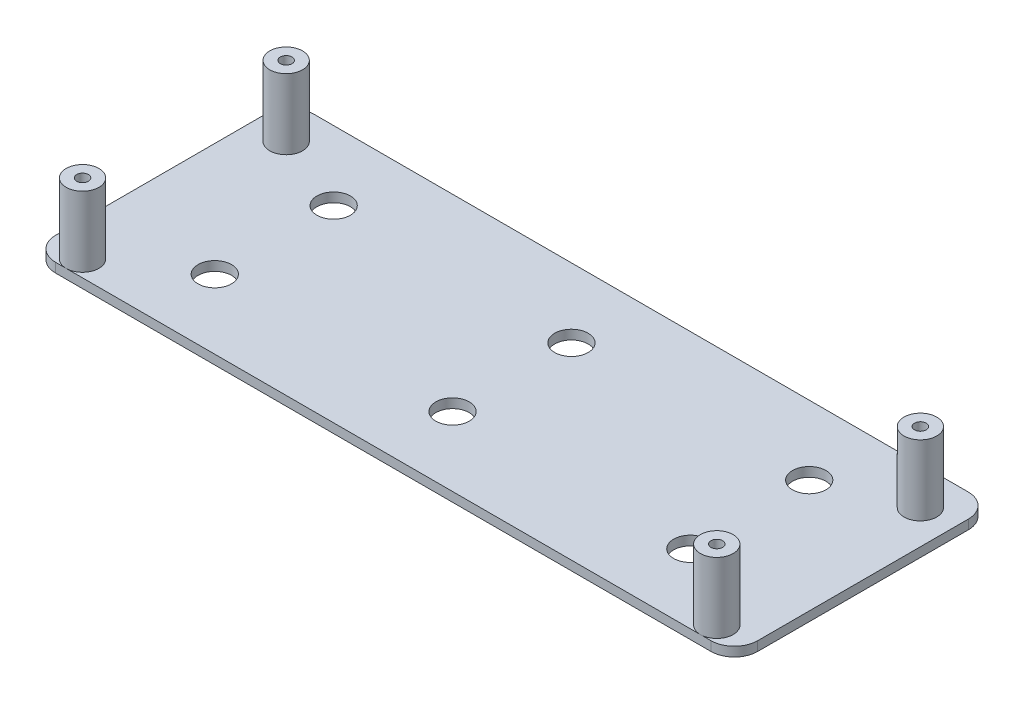
SolidWorks part; units mm, degrees
ref_plane "Front Plane" through (0, 0, 0) normal (0, 0, 1) x (1, 0, 0)
ref_plane "Top Plane" through (0, 0, 0) normal (0, 1, 0) x (1, 0, 0)
ref_plane "Right Plane" through (0, 0, 0) normal (1, 0, 0) x (0, 0, -1)
sketch "Sketch1" plane through (0, 0, 0) normal (0, 1, 0) x (1, 0, 0)
  line L1 (-75, -27.5) -> (75, -27.5)
  line L2 (-75, -27.5) -> (-75, 27.5)
  line L3 (-75, 27.5) -> (75, 27.5)
  line L4 (75, -27.5) -> (75, 27.5)
  line L5 (-75, -27.5) -> (75, 27.5) construction
  line L6 (-75, 27.5) -> (75, -27.5) construction
  line L7 (-67.75, -24) -> (67.75, -24) construction
  line L8 (-67.75, -24) -> (-67.75, 19.5) construction
  line L9 (-67.75, 19.5) -> (67.75, 19.5) construction
  line L10 (67.75, -24) -> (67.75, 19.5) construction
  point P0 (0, 0)
  point P10 (0, 19.5)
  dimension "D1" = 55
  dimension "D2" = 150
  dimension "D3" = 135.5
  dimension "D4" = 43.5
  dimension "D5" = 3.5
extrude "Boss-Extrude1" add sketch "Sketch1" along normal blind 2
sketch "Sketch2" plane through (0, 2, 0) normal (0, 1, 0) x (1, 0, 0)
  line L0 (-67.75, -24) -> (-67.75, 19.5) construction
  line L1 (-67.75, -24) -> (67.75, -24) construction
  line L2 (67.75, -24) -> (67.75, 19.5) construction
  line L3 (-67.75, 19.5) -> (67.75, 19.5) construction
  line L4 (-67.75, -24) -> (-67.75, 19.5) construction
  line L5 (-67.75, -24) -> (67.75, -24) construction
  line L6 (67.75, -24) -> (67.75, 19.5) construction
  line L7 (-67.75, 19.5) -> (67.75, 19.5) construction
  line L9 (-75, -27.5) -> (75, -27.5) construction
  circle A0 centre (-67.75, -24) radius 3.5
  circle A1 centre (-67.75, 19.5) radius 3.5
  circle A2 centre (67.75, 19.5) radius 3.5
  circle A3 centre (67.75, -24) radius 3.5
extrude "Boss-Extrude2" add sketch "Sketch2" along normal blind 15
sketch "Sketch3" plane through (0, 17, 0) normal (0, 1, 0) x (1, 0, 0)
  circle A0 centre (-67.75, -24) radius 1.25
  circle A1 centre (-67.75, 19.5) radius 1.25
  circle A2 centre (67.75, 19.5) radius 1.25
  circle A3 centre (67.75, -24) radius 1.25
  dimension "D1" = 2.5
extrude "Cut-Extrude1" cut sketch "Sketch3" against normal up to next
fillet "Fillet1" radius 5 4 edges at (-75, 1, -27.5) (75, 1, -27.5) (75, 1, 27.5) (-75, 1, 27.5)
hole_wizard "1/4 Clearance Hole1" positions "Sketch6" profile "Sketch7" hole size "1/4" standard "ANSI Inch" end condition up to next
sketch "Sketch6" plane through (0, 2, 0) normal (0, 1, 0) x (1, 0, 0)
  point P0 (-50.8, 12.7)
  point P2 (50.8, 12.7)
  point P4 (50.8, -12.7)
  point P6 (-50.8, -12.7)
  point P8 (0, -12.7)
  point P10 (0, 12.7)
  dimension "D1" = 25.4
  dimension "D2" = 12.7
  dimension "D3" = 50.8
  dimension "D4" = 50.8
sketch "Sketch7" plane through (-50.8, 2, -12.7) normal (1, 0, 0) x (0, 0, 1)
  line L0 (0, 0) -> (0, 2)
  line L1 (0, 2) -> (3.5712, 2)
  line L2 (3.5712, 2) -> (3.5712, 0)
  line L5 (3.5712, 0) -> (0, 0)
  line L11 (0, -6.35) -> (0, 107.95) construction
  dimension "Thru Hole Dia." = 7.1425
  dimension "Thru Hole Depth" = 2
sketch "Sketch8" plane through (0, 0, 0) normal (0, -1, 0) x (1, 0, 0)
  circle A0 centre (-67.75, 24) radius 2.1
  circle A1 centre (-67.75, -19.5) radius 2.1
  circle A2 centre (67.75, -19.5) radius 2.1
  circle A3 centre (67.75, 24) radius 2.1
  dimension "D1" = 4.2
extrude "Cut-Extrude2" cut sketch "Sketch8" against normal blind 10
